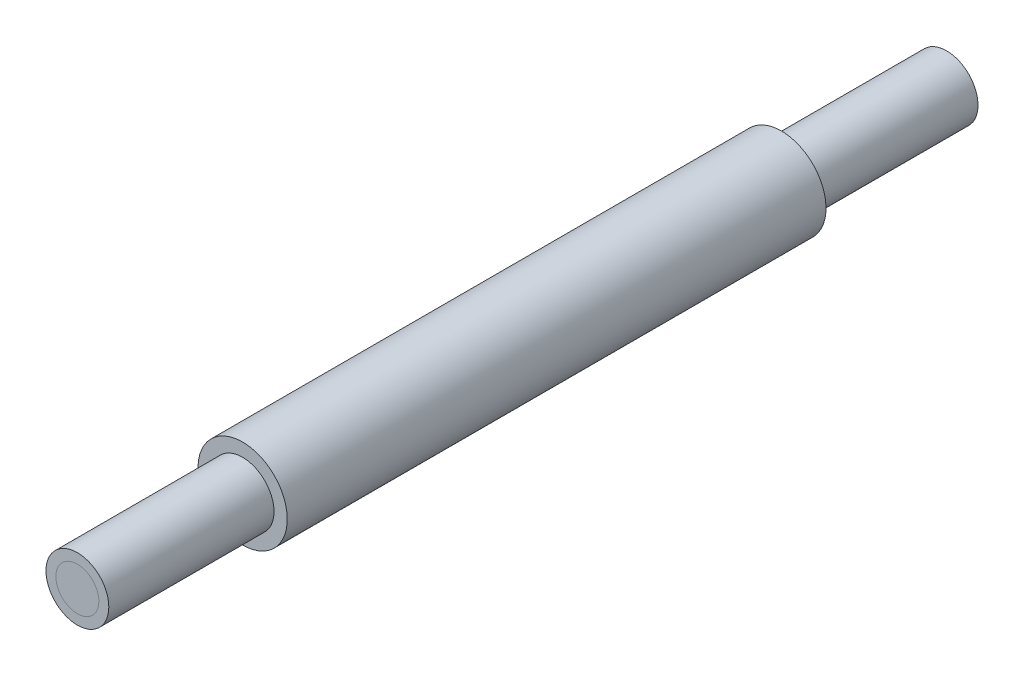
SolidWorks part; units mm, degrees
ref_plane "Front Plane" through (0, 0, 0) normal (0, 0, 1) x (1, 0, 0)
ref_plane "Top Plane" through (0, 0, 0) normal (0, 1, 0) x (1, 0, 0)
ref_plane "Right Plane" through (0, 0, 0) normal (1, 0, 0) x (0, 0, -1)
sketch "Sketch2" plane through (0, 0, 0) normal (1, 0, 0) x (0, 0, -1)
  line L0 (-1.8322, 0) -> (1.9889, 0) construction
  line L1 (-1.315, 0) -> (-1.315, 0.095)
  line L2 (-1.315, 0.095) -> (-0.815, 0.095)
  line L3 (-0.815, 0.095) -> (-0.815, 0.135)
  line L4 (-0.815, 0.135) -> (0.815, 0.135)
  line L5 (0, 0.5321) -> (0, -0.3301) construction
  line L6 (1.315, 0) -> (1.315, 0.095)
  line L7 (1.315, 0.095) -> (0.815, 0.095)
  line L8 (0.815, 0.095) -> (0.815, 0.135)
  line L9 (-1.315, 0) -> (1.315, 0)
  point P8 (-1.9889, 0)
  dimension "D1" = 0.095
  dimension "D2" = 0.5
  dimension "D3" = 1.63
  dimension "D4" = 2.63
  dimension "D5" = 0.04
revolve "Revolve1" add sketch "Sketch2" angle 360 about L9
chamfer "Chamfer1" distance 0.03 angle 0.25 2 edges at (0, -0.095, -1.315) (0, -0.095, 1.315)
